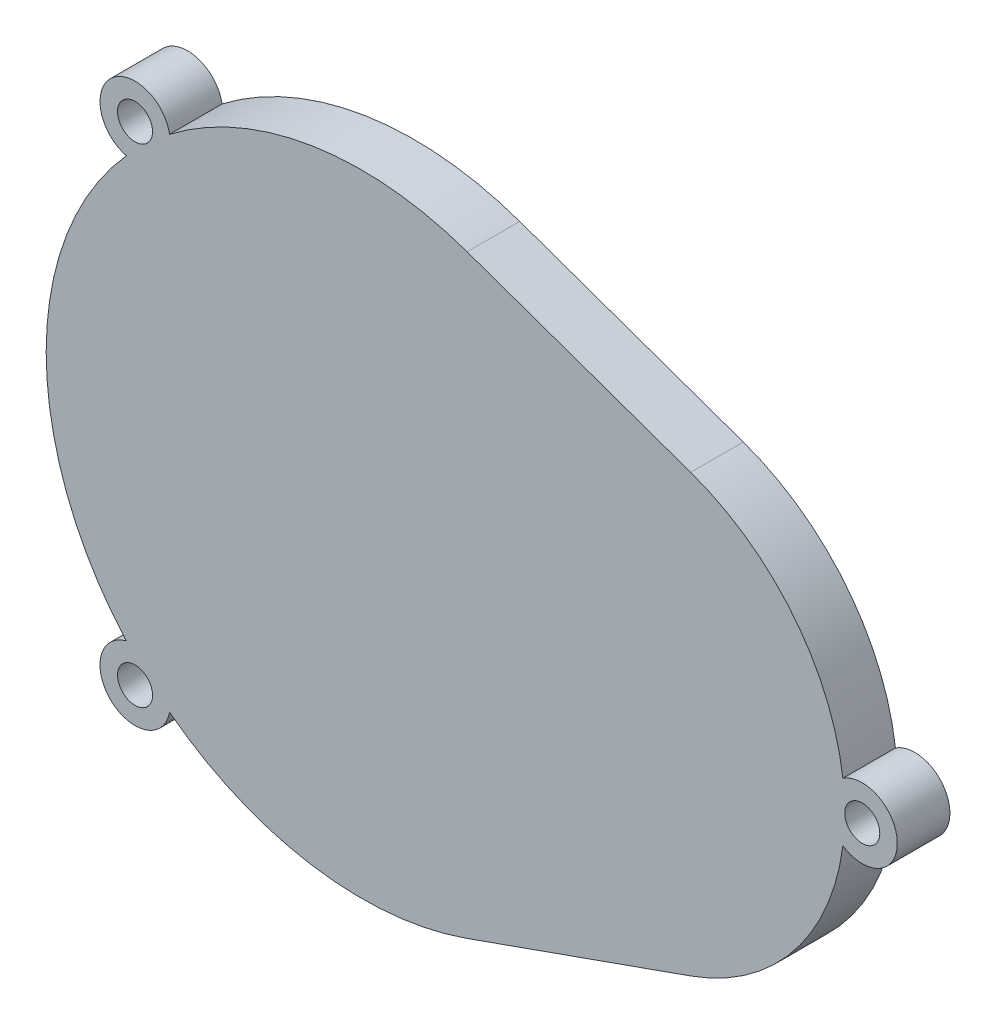
SolidWorks part; units mm, degrees
ref_plane "Front Plane" through (0, 0, 0) normal (0, 0, 1) x (1, 0, 0)
ref_plane "Top Plane" through (0, 0, 0) normal (0, 1, 0) x (1, 0, 0)
ref_plane "Right Plane" through (0, 0, 0) normal (1, 0, 0) x (0, 0, -1)
sketch "Sketch1" plane through (0, 0, 0) normal (0, 0, 1) x (1, 0, 0)
  line L0 (12.3649, 9.6877) -> (5.9872, 11.9497)
  line L1 (5.9872, -5.015) -> (12.3649, -2.753)
  arc A1 (12.3649, -2.753) -> (16.706, 2.634) centre (10.1588, 3.4673) ccw
  arc A2 (5.9872, 11.9497) -> (-2.5017, 10.6062) centre (2.9788, 3.4673) ccw
  circle A3 centre (-3.4858, 10.4285) radius 0.5
  arc A4 (-2.5017, 10.6062) -> (-3.7357, 9.4602) centre (-3.4858, 10.4285) ccw
  circle A5 centre (-3.4858, -3.4939) radius 0.5
  arc A6 (-3.7357, -2.5256) -> (-2.5017, -3.6715) centre (-3.4858, -3.4939) ccw
  arc A7 (16.706, 2.634) -> (16.706, 4.3006) centre (17.2588, 3.4673) ccw
  arc A9 (-3.7357, 9.4602) -> (-3.7357, -2.5256) centre (2.9788, 3.4673) ccw
  arc A10 (-2.5017, -3.6715) -> (5.9872, -5.015) centre (2.9788, 3.4673) ccw
  arc A12 (16.706, 4.3006) -> (12.3649, 9.6877) centre (10.1588, 3.4673) ccw
  circle A13 centre (17.2588, 3.4673) radius 0.5
  dimension "D1" = 1
  dimension "D2" = 1
  dimension "D3" = 1
  dimension "D4" = 1
  dimension "D5" = 1
  dimension "D6" = 1
  dimension "D8" = 9
extrude "Boss-Extrude1" add sketch "Sketch1" along normal blind 1.5
